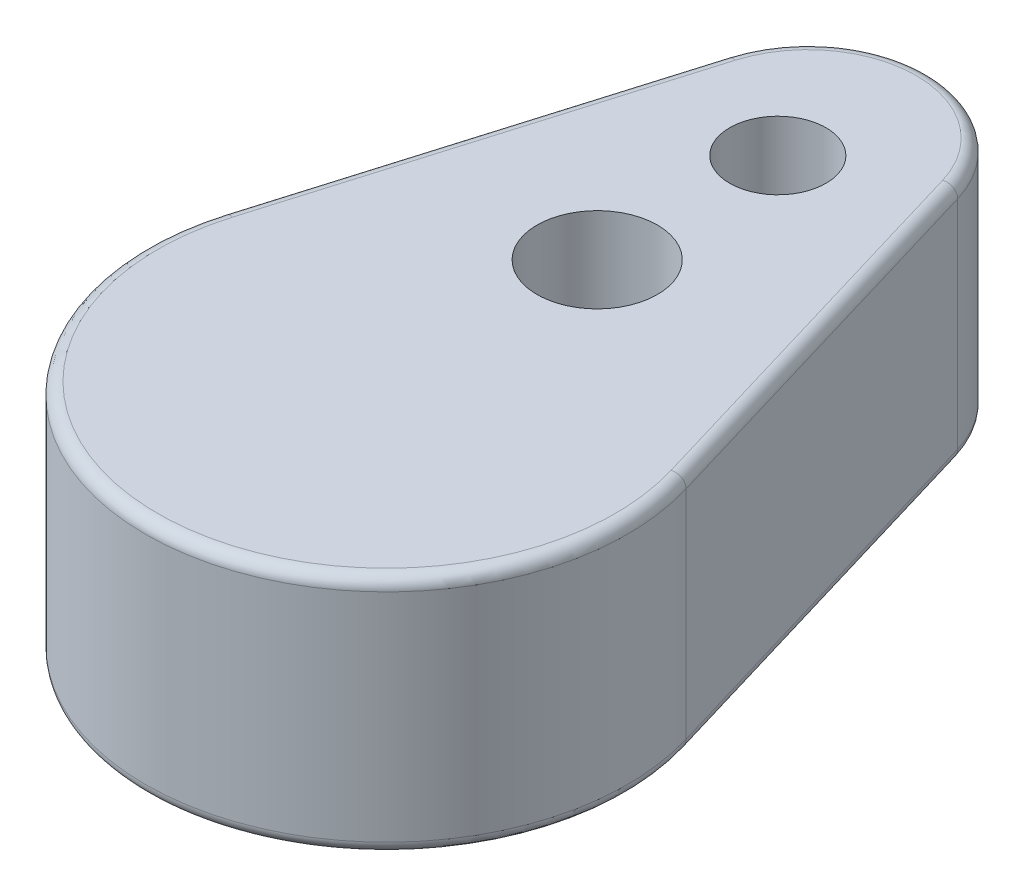
SolidWorks part; units mm, degrees
ref_plane "Front Plane" through (0, 0, 0) normal (0, 0, 1) x (1, 0, 0)
ref_plane "Top Plane" through (0, 0, 0) normal (0, 1, 0) x (1, 0, 0)
ref_plane "Right Plane" through (0, 0, 0) normal (1, 0, 0) x (0, 0, -1)
sketch "Sketch1" plane through (0, 0, 0) normal (0, 1, 0) x (1, 0, 0)
  line L0 (-9.5831, 20.3571) -> (-19.1663, -11.7857)
  line L1 (9.5831, 20.3571) -> (19.1663, -11.7857)
  arc A0 (9.5831, 20.3571) -> (-9.5831, 20.3571) centre (0, 17.5) ccw
  arc A1 (-19.1663, -11.7857) -> (19.1663, -11.7857) centre (0, -17.5) ccw
  dimension "D1" = 20
  dimension "D2" = 40
  dimension "D3" = 35
  dimension "D4" = 17.5
extrude "Boss-Extrude1" add sketch "Sketch1" along normal blind 20
fillet "Fillet1" radius 1 8 edges at (0, 0, -27.5) (14.3747, 0, -4.2857) (0, 0, 37.5) (0, 20, -27.5) (14.3747, 20, -4.2857) (0, 20, 37.5) (-14.3747, 0, -4.2857) (-14.3747, 20, -4.2857)
sketch "Sketch2" plane through (0, 0, 0) normal (0, 1, 0) x (1, 0, 0)
  circle A0 centre (0, 15) radius 4
  dimension "D1" = 15
  dimension "D2" = 8
extrude "Cut-Extrude1" cut sketch "Sketch2" along normal blind 15
sketch "Sketch3" plane through (0, 20, 0) normal (0, -1, 0) x (1, 0, 0)
  circle A0 centre (0, 0) radius 5
  dimension "D1" = 10
extrude "Cut-Extrude2" cut sketch "Sketch3" along normal blind 15
sketch "Sketch4" plane through (0, 5, 0) normal (0, 1, 0) x (-1, 0, 0)
  circle A0 centre (0, 0) radius 4.1
  circle A1 centre (0, -15) radius 4
  dimension "D1" = 8.2
  dimension "D2" = 8
  dimension "D3" = 15
extrude "Cut-Extrude3" cut sketch "Sketch4" against normal through all both and the other way through all
